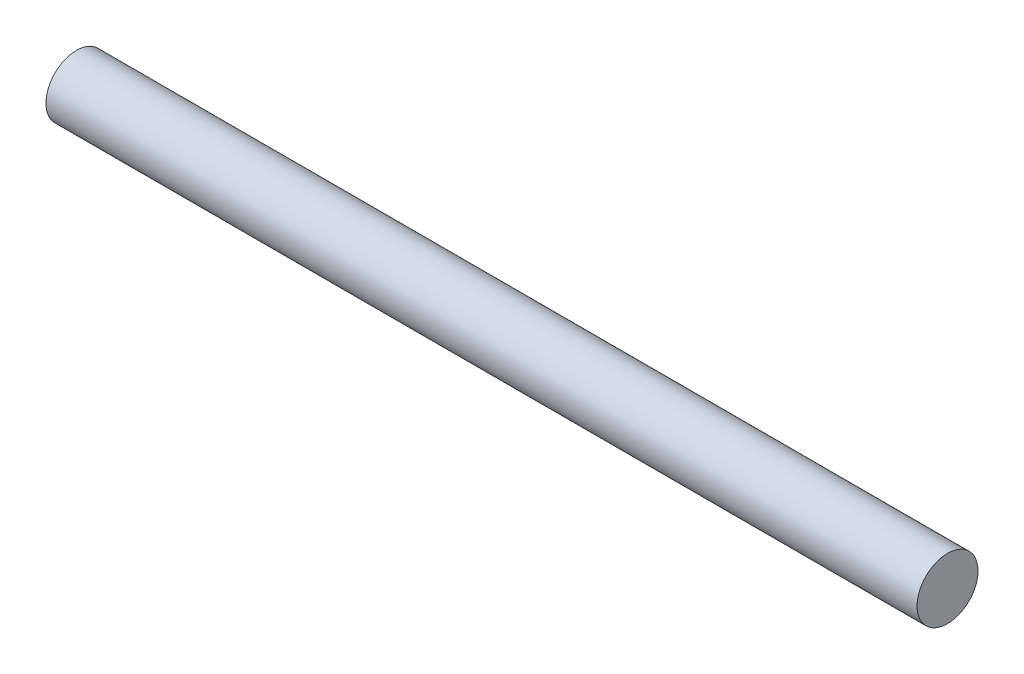
SolidWorks part; units mm, degrees
material "Stainless Steel (ferritic)"
ref_plane "Front Plane" through (0, 0, 0) normal (0, 0, 1) x (1, 0, 0)
ref_plane "Top Plane" through (0, 0, 0) normal (0, 1, 0) x (1, 0, 0)
ref_plane "Right Plane" through (0, 0, 0) normal (1, 0, 0) x (0, 0, -1)
sketch "Sketch1" plane through (0, 0, 0) normal (1, 0, 0) x (0, 0, -1)
  circle A0 centre (0, 0) radius 35
extrude "Boss-Extrude1" add sketch "Sketch1" along normal blind 1000
